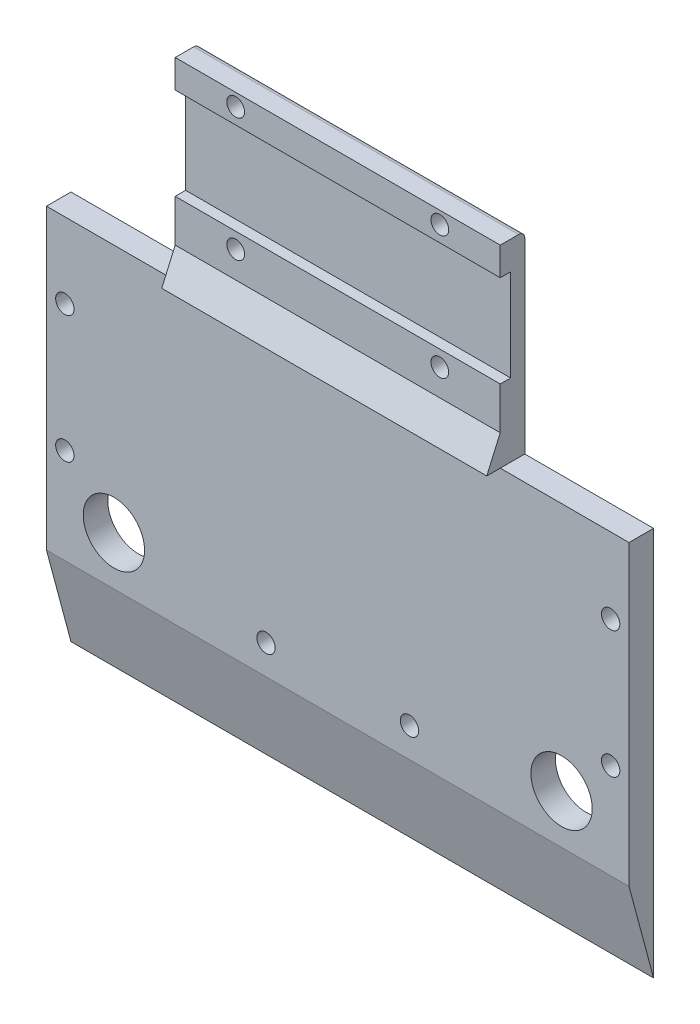
SolidWorks part; units mm, degrees
ref_plane "Alzado" through (0, 0, 0) normal (0, 0, 1) x (1, 0, 0)
ref_plane "Planta" through (0, 0, 0) normal (0, 1, 0) x (1, 0, 0)
ref_plane "Vista lateral" through (0, 0, 0) normal (1, 0, 0) x (0, 0, -1)
sketch "Croquis1" plane through (0, 0, 0) normal (0, 0, 1) x (1, 0, 0)
  line L1 (9.2769, 17.9764) -> (104.2769, 17.9764)
  line L2 (9.2769, 17.9764) -> (9.2769, -77.0236)
  line L3 (9.2769, -77.0236) -> (104.2769, -77.0236)
  line L4 (104.2769, 17.9764) -> (104.2769, -77.0236)
  dimension "D1" = 95
  dimension "D2" = 95
extrude "Saliente-Extruir1" add sketch "Croquis1" along normal blind 4 contours L3 L4 L1 L2
sketch "Croquis3" plane through (9.2769, 0, 0) normal (-1, 0, 0) x (0, 0, 1)
  line L0 (0, -77.0236) -> (4, -62.0765)
  line L1 (4, 17.9764) -> (4, -77.0236) construction
  line L2 (4, -77.0236) -> (4, -62.0765)
  line L3 (4, -77.0236) -> (0, -77.0236)
  line L4 (4, -62.0765) -> (0, -62.0765)
  line L5 (0, 17.9764) -> (0, -77.0236) construction
  line L6 (0, -62.0765) -> (0, -77.0236)
  line M2 (0, -77.0236) -> (4, -77.0236)
  line M3 (4, -77.0236) -> (4, 17.9764)
extrude "Cortar-Extruir1" cut sketch "Croquis3" against normal blind 100 contours L0 M2 M3
sketch "Croquis5" plane through (0, 0, 4) normal (0, 0, 1) x (1, 0, 0)
  line L1 (9.2769, 17.9764) -> (30.2769, 17.9764)
  line L2 (9.2769, 17.9764) -> (9.2769, -13.5236)
  line L3 (9.2769, -13.5236) -> (30.2769, -13.5236)
  line L4 (30.2769, 17.9764) -> (30.2769, -13.5236)
  dimension "D1" = 31.5
  dimension "D2" = 21
extrude "Cortar-Extruir2" cut sketch "Croquis5" against normal blind 100
sketch "Croquis6" plane through (0, 0, 4) normal (0, 0, 1) x (1, 0, 0)
  line L1 (104.2769, 17.9764) -> (83.2769, 17.9764)
  line L2 (104.2769, 17.9764) -> (104.2769, -13.5236)
  line L3 (104.2769, -13.5236) -> (83.2769, -13.5236)
  line L4 (83.2769, 17.9764) -> (83.2769, -13.5236)
  dimension "D1" = 31.5
  dimension "D2" = 21
extrude "Cortar-Extruir3" cut sketch "Croquis6" against normal blind 100
sketch "Croquis7" plane through (30.2769, 0, 0) normal (-1, 0, 0) x (0, 0, 1)
  line L1 (5.3084, 13.3674) -> (2.3084, 13.3674)
  line L2 (5.3084, 13.3674) -> (5.3084, -1.6326)
  line L3 (5.3084, -1.6326) -> (2.3084, -1.6326)
  line L4 (2.3084, 13.3674) -> (2.3084, -1.6326)
  dimension "D1" = 3
  dimension "3.6" = 15
extrude "Cortar-Extruir4" cut sketch "Croquis7" against normal blind 100
fillet "Redondeo1" radius 1 1 edges at (56.7769, 17.9764, 0)
sketch "Croquis8" plane through (0, 0, 0) normal (0, 0, -1) x (-1, 0, 0)
  line L10 (-104.2769, -13.5236) -> (-104.2769, -77.0236) construction
  line L11 (-9.2769, -13.5236) -> (-9.2769, -77.0236) construction
  circle A0 centre (-93.2769, -54.1309) radius 5
  circle A1 centre (-20.2769, -54.1309) radius 5
  dimension "D1" = 11
  dimension "D2" = 11
  dimension "D3" = 10
extrude "Cortar-Extruir5" cut sketch "Croquis8" against normal blind 10
sketch "Croquis9" plane through (30.2769, 0, 0) normal (-1, 0, 0) x (0, 0, 1)
  line L0 (4, -13.5236) -> (4, -8.5236)
  line L1 (4, -13.5236) -> (4, -1.6326) construction
  line L2 (4, -8.5236) -> (6.2, -13.5236)
  line L3 (6.2, -13.5236) -> (4, -13.5236)
  dimension "D1" = 2.2
  dimension "D2" = 5
extrude "Saliente-Extruir2" add sketch "Croquis9" against normal blind 53
sketch "Croquis10" plane through (0, 0, 4) normal (0, 0, 1) x (1, 0, 0)
  line L0 (12.2769, -13.5236) -> (12.2769, -25.8236) construction
  line L1 (9.2769, -13.5236) -> (30.2769, -13.5236) construction
  line L2 (9.2769, -13.5236) -> (9.2769, -62.0765) construction
  line L3 (104.2769, -62.0765) -> (9.2769, -62.0765) construction
  line L4 (56.7769, -13.5236) -> (56.7769, -62.0765) construction
  line L5 (83.2769, -13.5236) -> (30.2769, -13.5236) construction
  circle A0 centre (12.2769, -25.8236) radius 1.5
  circle A1 centre (12.2769, -46.5236) radius 1.5
  circle A2 centre (45.0769, -57.2765) radius 1.5
  circle A3 centre (68.4769, -57.2765) radius 1.5
  circle A4 centre (101.2769, -25.8236) radius 1.5
  circle A5 centre (101.2769, -46.5236) radius 1.5
  dimension "D2" = 3
  dimension "D3" = 3
  dimension "D4" = 3
  dimension "D5" = 20.7
  dimension "D6" = 35.8
  dimension "D7" = 3
  dimension "D8" = 4.8
  dimension "D1" = 12.3
extrude "Cortar-Extruir6" cut sketch "Croquis10" against normal blind 10
sketch "Croquis11" plane through (0, 0, 4) normal (0, 0, 1) x (1, 0, 0)
  circle A0 centre (40.1297, 15.9353) radius 1.45
  circle A1 centre (73.424, 15.9353) radius 1.45
  circle A2 centre (40.1297, -4.1824) radius 1.45
  circle A3 centre (73.424, -4.1824) radius 1.45
extrude "Cortar-Extruir7" cut sketch "Croquis11" against normal blind 20
